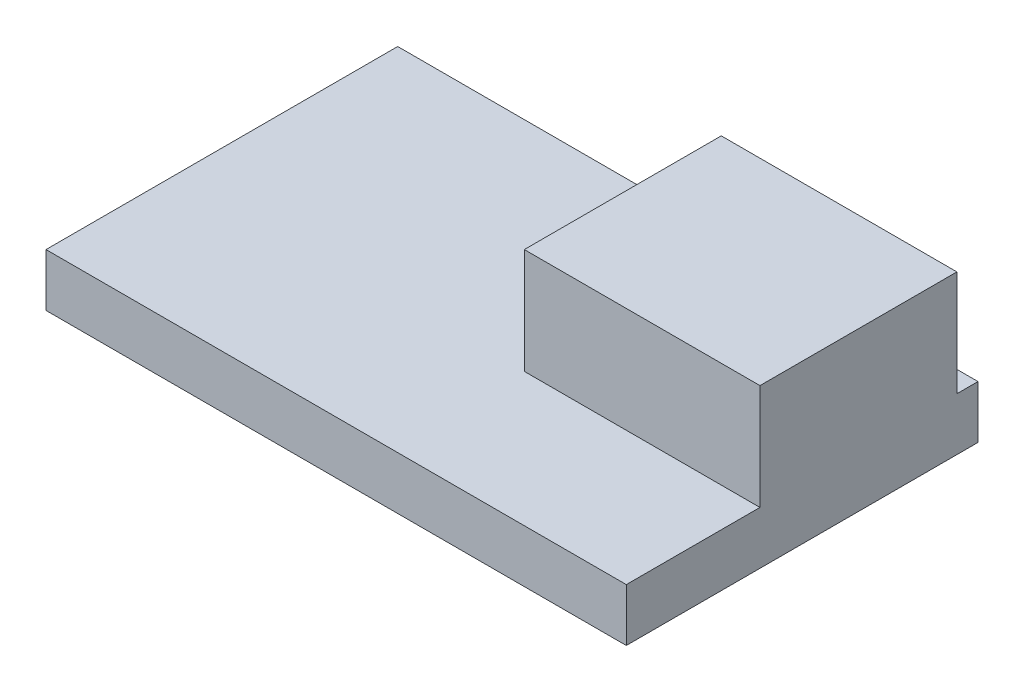
SolidWorks part; units mm, degrees
ref_plane "Front Plane" through (0, 0, 0) normal (0, 0, 1) x (1, 0, 0)
ref_plane "Top Plane" through (0, 0, 0) normal (0, 1, 0) x (1, 0, 0)
ref_plane "Right Plane" through (0, 0, 0) normal (1, 0, 0) x (0, 0, -1)
sketch "Sketch1" plane through (0, 0, 0) normal (0, 1, 0) x (1, 0, 0)
  line L1 (-22.7791, 23.3733) -> (142.2209, 23.3733)
  line L2 (-22.7791, 23.3733) -> (-22.7791, -76.6267)
  line L3 (-22.7791, -76.6267) -> (142.2209, -76.6267)
  line L4 (142.2209, 23.3733) -> (142.2209, -76.6267)
  dimension "D1" = 165
  dimension "D2" = 100
extrude "Boss-Extrude1" add sketch "Sketch1" along normal blind 45
sketch "Sketch2" plane through (0, 45, 0) normal (0, 1, 0) x (1, 0, 0)
  line L0 (142.2209, -76.6267) -> (142.2209, 23.3733) construction
  line L1 (75.2209, 17.3733) -> (142.2209, 17.3733)
  line L2 (75.2209, 17.3733) -> (75.2209, -38.6267)
  line L3 (75.2209, -38.6267) -> (142.2209, -38.6267)
  line L4 (142.2209, 17.3733) -> (142.2209, -38.6267)
  line L5 (142.2209, 23.3733) -> (-22.7791, 23.3733) construction
  line L7 (-22.7791, 23.3733) -> (142.2209, 23.3733)
  line L8 (-22.7791, 23.3733) -> (-22.7791, -76.6267)
  line L9 (-22.7791, -76.6267) -> (142.2209, -76.6267)
  line L10 (142.2209, 23.3733) -> (142.2209, -76.6267)
  line M5 (-22.7791, 23.3733) -> (-22.7791, -76.6267)
  line M6 (-22.7791, -76.6267) -> (142.2209, -76.6267)
  line M7 (142.2209, -76.6267) -> (142.2209, 23.3733)
  line M8 (142.2209, 23.3733) -> (-22.7791, 23.3733)
  dimension "D1" = 56
  dimension "D2" = 0
  dimension "D3" = 67
  dimension "D4" = 6
extrude "Cut-Extrude1" cut sketch "Sketch2" against normal blind 30 contours L3 L2 L1 M7 M8 M5 M6
